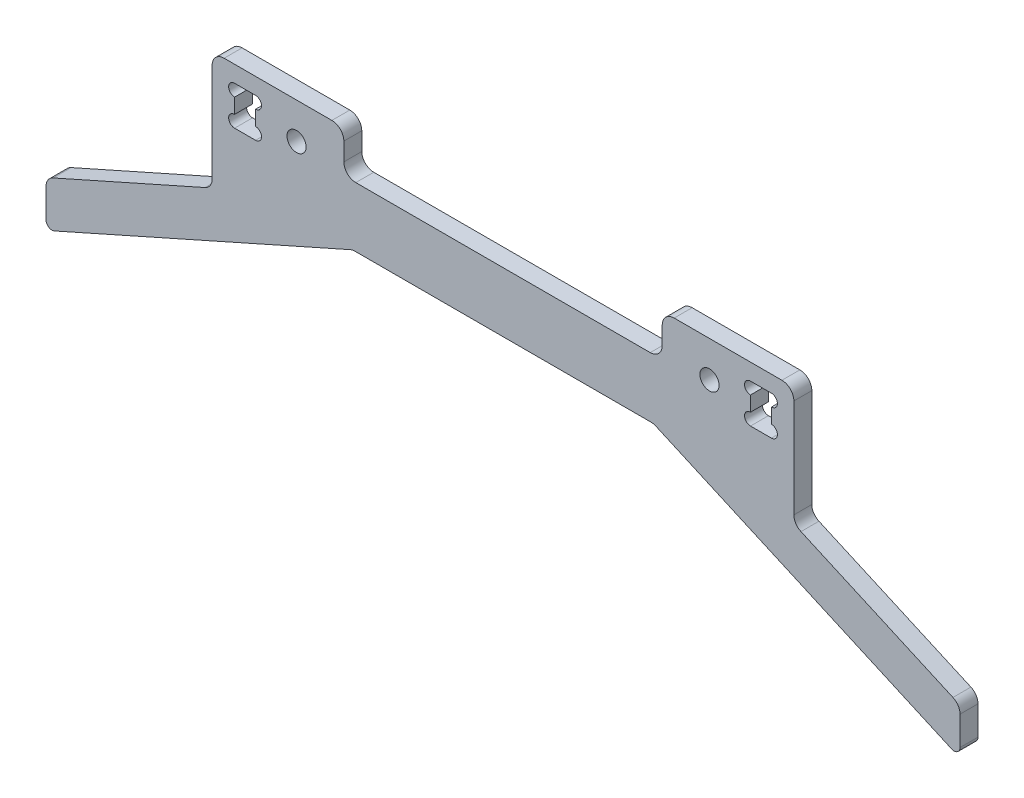
SolidWorks part; units mm, degrees
ref_plane "前视基准面" through (0, 0, 0) normal (0, 0, 1) x (1, 0, 0)
ref_plane "上视基准面" through (0, 0, 0) normal (0, 1, 0) x (1, 0, 0)
ref_plane "右视基准面" through (0, 0, 0) normal (1, 0, 0) x (0, 0, -1)
sketch "草图1" plane through (0, 0, 0) normal (0, 0, 1) x (1, 0, 0)
  line L0 (-89.12, 0) -> (89.12, 0) construction
  line L1 (0, 0) -> (0, 100) construction
  line L2 (76.3653, 0) -> (0, 34)
  line L3 (-76.3653, 0) -> (0, 34)
  line L4 (76.3653, 6.5678) -> (0, 40.5678)
  line L5 (-76.3653, 6.5678) -> (0, 40.5678)
  line L6 (76.3653, 0) -> (76.3653, 6.5678)
  line L7 (-76.3653, 0) -> (-76.3653, 6.5678)
  line L8 (-78.8057, 5.4813) -> (0, 40.5678) construction
  line L9 (78.8057, 5.4813) -> (0, 40.5678) construction
  dimension "D1" = 178.24
  dimension "D2" = 100
  dimension "D3" = 34
  dimension "D4" = 24
  dimension "D6" = 152.7305
  dimension "D5" = 6
extrude "凸台-拉伸1" add sketch "草图1" along normal blind 3
sketch "草图2" plane through (0, 0, 3) normal (0, 0, 1) x (1, 0, 0)
  line L0 (0, 40.5678) -> (0, 34) construction
  line L7 (0, 40.5678) -> (-76.3653, 6.5678) construction
  line L8 (-41.6, 22.0463) -> (41.6, 22.0463)
  line L9 (-41.6, 22.0463) -> (-41.6, 31.0463)
  line L10 (-41.6, 31.0463) -> (41.6, 31.0463)
  line L11 (41.6, 22.0463) -> (41.6, 31.0463)
  line L12 (76.3653, 6.5678) -> (0, 40.5678) construction
  dimension "D1" = 83.2
  dimension "D2" = 9
extrude "凸台-拉伸2" add sketch "草图2" against normal blind 3
sketch "草图3" plane through (0, 0, 3) normal (0, 0, 1) x (1, 0, 0)
  line L1 (-21.3857, 31.0463) -> (21.3857, 31.0463)
  line L2 (-21.3857, 31.0463) -> (-21.3857, 40.5678)
  line L3 (-21.3857, 40.5678) -> (21.3857, 40.5678)
  line L4 (21.3857, 31.0463) -> (21.3857, 40.5678)
extrude "切除-拉伸1" cut sketch "草图3" against normal blind 3
sketch "草图4" plane through (0, 0, 3) normal (0, 0, 1) x (1, 0, 0)
  line L0 (41.6, 31.0463) -> (48.6, 31.0463)
  line L1 (48.6, 31.0463) -> (48.6, 18.9297)
  line L2 (76.3653, 6.5678) -> (41.6, 22.0463) construction
  line L3 (48.6, 18.9297) -> (41.6, 22.0463)
  line L4 (41.6, 22.0463) -> (41.6, 31.0463)
  line L5 (-41.6, 31.0463) -> (-48.6, 31.0463)
  line L6 (-48.6, 31.0463) -> (-48.6, 18.9297)
  line L7 (-41.6, 22.0463) -> (-76.3653, 6.5678) construction
  line L8 (-48.6, 18.9297) -> (-41.6, 22.0463)
  line L9 (-41.6, 31.0463) -> (-41.6, 22.0463) construction
  line L10 (-41.6, 22.0463) -> (-41.6, 31.0463)
  dimension "D1" = 7
  dimension "D2" = 7
extrude "凸台-拉伸3" add sketch "草图4" against normal blind 3
sketch "草图5" plane through (0, 0, 3) normal (0, 0, 1) x (1, 0, 0)
  line L0 (0, 31.0463) -> (0, 22.0463) construction
  line L1 (48.6, 31.0463) -> (-48.6, 31.0463) construction
  line L2 (-26.8484, 22.0463) -> (26.8484, 22.0463) construction
  line L3 (-48.6, 31.0463) -> (-48.6, 18.9297) construction
  line L4 (-44.85, 28.2963) -> (-41.35, 28.2963)
  line L5 (-44.85, 26.2963) -> (-44.85, 23.7963)
  line L6 (-44.85, 21.7963) -> (-41.35, 21.7963)
  line L7 (-41.35, 26.2963) -> (-41.35, 23.7963)
  line L8 (41.35, 26.2963) -> (41.35, 23.7963)
  line L9 (44.85, 21.7963) -> (41.35, 21.7963)
  line L10 (44.85, 26.2963) -> (44.85, 23.7963)
  line L11 (44.85, 28.2963) -> (41.35, 28.2963)
  arc A0 (-44.85, 28.2963) -> (-44.85, 26.2963) centre (-44.85, 27.2963) ccw
  arc A1 (-41.35, 26.2963) -> (-41.35, 28.2963) centre (-41.35, 27.2963) ccw
  arc A2 (-41.35, 21.7963) -> (-41.35, 23.7963) centre (-41.35, 22.7963) ccw
  arc A3 (-44.85, 23.7963) -> (-44.85, 21.7963) centre (-44.85, 22.7963) ccw
  arc A4 (44.85, 23.7963) -> (44.85, 21.7963) centre (44.85, 22.7963) cw
  arc A5 (41.35, 21.7963) -> (41.35, 23.7963) centre (41.35, 22.7963) cw
  arc A6 (41.35, 26.2963) -> (41.35, 28.2963) centre (41.35, 27.2963) cw
  arc A7 (44.85, 28.2963) -> (44.85, 26.2963) centre (44.85, 27.2963) cw
  dimension "D5" = 2
  dimension "D1" = 6.5
  dimension "D2" = 3.5
  dimension "D3" = 2.75
  dimension "D4" = 3.75
extrude "切除-拉伸2" cut sketch "草图5" against normal blind 3
sketch "草图7" plane through (0, 0, 3) normal (0, 0, 1) x (1, 0, 0)
  line L0 (26.8484, 22.0463) -> (76.3653, 0) construction
  line L2 (-76.3653, 0) -> (-26.8484, 22.0463) construction
  line L3 (26.8484, 22.0463) -> (76.3653, 0)
  line L4 (-26.8484, 22.0463) -> (26.8484, 22.0463)
  line L5 (-76.3653, 0) -> (-26.8484, 22.0463)
  line L6 (-76.3653, -8.7571) -> (-25.148, 14.0463)
  line L7 (-25.148, 14.0463) -> (25.148, 14.0463)
  line L8 (25.148, 14.0463) -> (76.3653, -8.7571)
  line L9 (-73.1114, -7.3084) -> (-25.148, 14.0463) construction
  line L10 (25.148, 14.0463) -> (73.1114, -7.3084) construction
  line L11 (76.3653, 0) -> (76.3653, 6.5678) construction
  line L12 (-76.3653, 6.5678) -> (-76.3653, 0) construction
  line L13 (-76.3653, -8.7571) -> (-76.3653, 0)
  line L14 (76.3653, -8.7571) -> (76.3653, 0)
  dimension "D1" = 8
extrude "凸台-拉伸4" add sketch "草图7" against normal blind 3
sketch "草图6" plane through (0, 0, 0) normal (0, 0, -1) x (-1, 0, 0)
  line L0 (0, 31.0463) -> (0, 14.0463) construction
  line L1 (-48.6, 31.0463) -> (48.6, 31.0463) construction
  line L2 (25.148, 14.0463) -> (-25.148, 14.0463) construction
  circle A1 centre (-34.5, 25.0463) radius 1.6
  circle A2 centre (34.5, 25.0463) radius 1.6
  dimension "D1" = 6
  dimension "D2" = 3.2
  dimension "D3" = 69
extrude "切除-拉伸3" cut sketch "草图6" against normal blind 3
sketch "草图8" plane through (0, 0, 3) normal (0, 0, 1) x (1, 0, 0)
  line L0 (-76.3653, -1.0946) -> (-48.6, 11.2672)
  line L1 (-76.3653, 6.5678) -> (-76.3653, -8.7571) construction
  line L2 (-48.6, 11.2672) -> (-48.6, 18.9297)
  line L3 (-48.6, 18.9297) -> (-76.3653, 6.5678)
  line L4 (-76.3653, 6.5678) -> (-76.3653, -1.0946)
  line L5 (-26.6, 31.0463) -> (-26.6, 24.0463)
  line L6 (48.6, 31.0463) -> (-48.6, 31.0463) construction
  line L7 (-26.6, 24.0463) -> (26.6, 24.0463)
  line L8 (26.6, 24.0463) -> (26.6, 31.0463)
  line L9 (26.6, 31.0463) -> (-26.6, 31.0463)
  line L10 (48.6, 18.9297) -> (76.3653, 6.5678)
  line L11 (76.3653, 6.5678) -> (48.6, 18.9297) construction
  line L12 (76.3653, 6.5678) -> (76.3653, -1.0946)
  line L13 (76.3653, -8.7571) -> (76.3653, 6.5678) construction
  line L14 (76.3653, -1.0946) -> (48.6, 11.2672)
  line L15 (48.6, 11.2672) -> (48.6, 18.9297)
  line L16 (-48.6, 18.9297) -> (-76.3653, 6.5678) construction
  line L17 (-48.6, 31.0463) -> (-48.6, 18.9297) construction
  line L18 (48.6, 18.9297) -> (48.6, 31.0463) construction
  point P27 (26.6, 27.5463)
  dimension "D1" = 7
  dimension "D2" = 7
  dimension "D3" = 7
  dimension "D4" = 22
  dimension "D5" = 22
extrude "切除-拉伸4" cut sketch "草图8" against normal blind 10
fillet "圆角2" radius 2 12 edges at (25.148, 14.0463, 1.5) (-25.148, 14.0463, 1.5) (-26.6, 31.0463, 1.5) (26.6, 31.0463, 1.5) (-76.3653, -1.0946, 1.5) (-48.6, 11.2672, 1.5) (26.6, 24.0463, 1.5) (-26.6, 24.0463, 1.5) (48.6, 11.2672, 1.5) (76.3653, -1.0946, 1.5) (48.6, 31.0463, 1.5) (-48.6, 31.0463, 1.5)
fillet "圆角3" radius 1 2 edges at (76.3653, -8.7571, 1.5) (-76.3653, -8.7571, 1.5)
